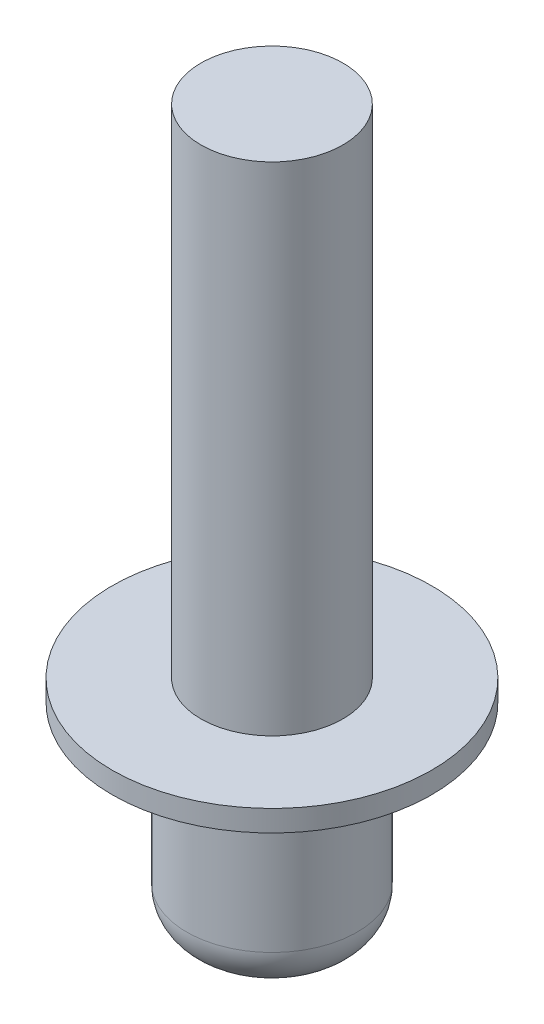
SolidWorks part; units mm, degrees
ref_plane "Front Plane" through (0, 0, 0) normal (0, 0, 1) x (1, 0, 0)
ref_plane "Top Plane" through (0, 0, 0) normal (0, 1, 0) x (1, 0, 0)
ref_plane "Right Plane" through (0, 0, 0) normal (1, 0, 0) x (0, 0, -1)
sketch "Sketch1" plane through (0, 0, 0) normal (0, 1, 0) x (1, 0, 0)
  circle A0 centre (0, 0) radius 22.5
  dimension "D1" = 45
extrude "Boss-Extrude3" add sketch "Sketch1" along normal blind 3
sketch "Sketch2" plane through (0, 3, 0) normal (0, 1, 0) x (1, 0, 0)
  circle A0 centre (0, 0) radius 10
extrude "Boss-Extrude5" add sketch "Sketch2" along normal blind 70
sketch "Sketch4" plane through (0, 0, 0) normal (0, -1, 0) x (1, 0, 0)
sketch "Sketch5" plane through (0, 0, 0) normal (0, -1, 0) x (1, 0, 0)
  circle A0 centre (0, 0) radius 12
extrude "Boss-Extrude6" add sketch "Sketch5" along normal blind 28
fillet "Fillet1" radius 6 1 edges at (0, -28, -12)
sketch "Sketch6" plane through (0, 0, 0) normal (0, 0, 1) x (1, 0, 0)
  line L0 (0, 0) -> (0, -28) construction
  line L1 (-6, -28) -> (6, -28) construction
  line L2 (-35.7283, -28) -> (35.7283, -28)
  line L3 (35.7283, -28) -> (35.7283, -5.0194)
  line L4 (35.7283, -5.0194) -> (4.9253, -5.0194)
  line L5 (4.9253, -5.0194) -> (4.9253, -28)
  line L6 (-4.9253, -5.0194) -> (-4.9253, -28)
  line L7 (-35.7283, -28) -> (-35.7283, -5.0194)
  line L8 (-35.7283, -5.0194) -> (-4.9253, -5.0194)
  point P13 (0, -28)
